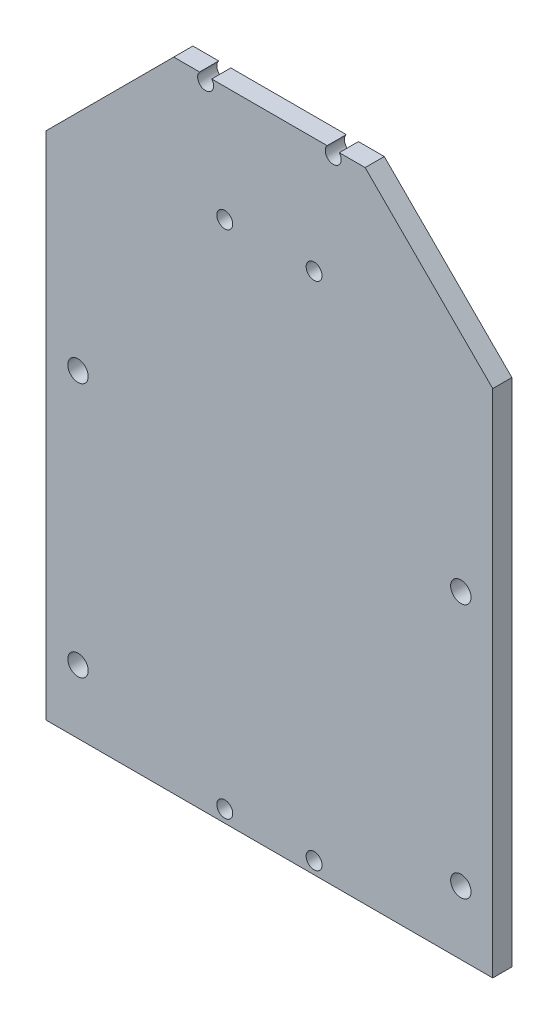
SolidWorks part; units mm, degrees
material "Thornel Mat VMA"
ref_plane "前视基准面" through (0, 0, 0) normal (0, 0, 1) x (1, 0, 0)
ref_plane "上视基准面" through (0, 0, 0) normal (0, 1, 0) x (1, 0, 0)
ref_plane "右视基准面" through (0, 0, 0) normal (1, 0, 0) x (0, 0, -1)
sketch "草图1" plane through (0, 0, 0) normal (0, 0, 1) x (1, 0, 0)
  line L1 (-79.2332, 22.3507) -> (-9.2332, 22.3507)
  line L2 (-79.2332, 22.3507) -> (-79.2332, 122.3507)
  line L3 (-79.2332, 122.3507) -> (-9.2332, 122.3507)
  line L4 (-9.2332, 22.3507) -> (-9.2332, 122.3507)
  dimension "D1" = 70
  dimension "D2" = 100
extrude "凸台-拉伸1" add sketch "草图1" along normal blind 3
sketch "草图2" plane through (0, 0, 3) normal (0, 0, 1) x (1, 0, 0)
  circle A2 centre (-74.2332, 32.3507) radius 1.6
  circle A3 centre (-14.2332, 32.3507) radius 1.6
  circle A4 centre (-14.2332, 72.2862) radius 1.6
  circle A5 centre (-74.2332, 72.2862) radius 1.6
extrude "切除-拉伸1" cut sketch "草图2" against normal blind 3
sketch "草图3" plane through (0, 0, 0) normal (0, 0, -1) x (-1, 0, 0)
  circle A0 centre (37.2331, 104.2862) radius 1.25
  circle A1 centre (51.2331, 104.2862) radius 1.25
  circle A2 centre (37.2331, 24.2862) radius 1.25
  circle A3 centre (51.2331, 24.2862) radius 1.25
  circle A4 centre (34.2332, 121.5362) radius 1.25
  circle A5 centre (54.2332, 121.5362) radius 1.25
  dimension "D1" = 2.5
extrude "切除-拉伸2" cut sketch "草图3" against normal blind 3
chamfer "倒角1" distance 20 angle 45 2 edges at (-79.2332, 122.3507, 1.5) (-9.2332, 122.3507, 1.5)
